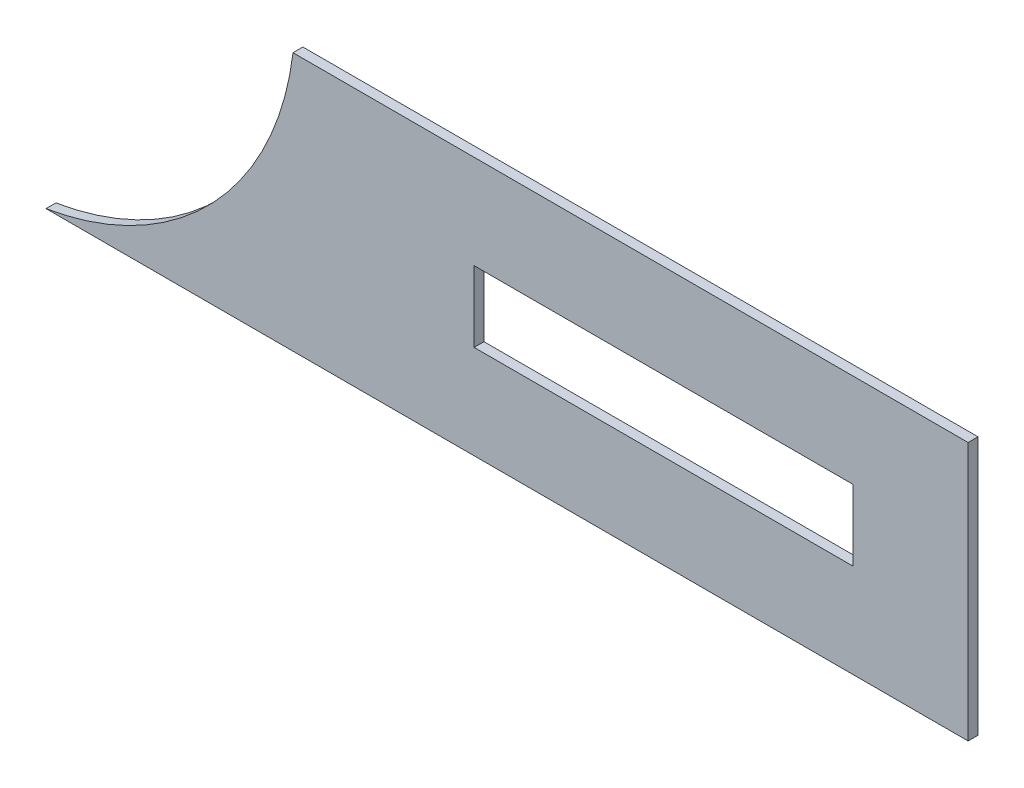
SolidWorks part; units mm, degrees
ref_plane "Спереди" through (0, 0, 0) normal (0, 0, 1) x (1, 0, 0)
ref_plane "Сверху" through (0, 0, 0) normal (0, 1, 0) x (1, 0, 0)
ref_plane "Справа" through (0, 0, 0) normal (1, 0, 0) x (0, 0, -1)
sketch "Эскиз1" plane through (0, 0, 0) normal (0, 0, 1) x (1, 0, 0)
  line L1 (0, 0) -> (56, 0)
  line L2 (26, 5.7) -> (49, 5.7)
  line L3 (15, 15.7) -> (56, 15.7)
  line L4 (56, 0) -> (56, 15.7)
  line L5 (26, 5.7) -> (26, 10)
  line L6 (26, 10) -> (49, 10)
  line L7 (49, 5.7) -> (49, 10)
  arc A0 (0, 0) -> (15, 15.7) centre (-2.9872, 17.8697) ccw
  point P10 (56, 7.85)
  point P11 (49, 7.85)
  dimension "D3" = 41
  dimension "D1" = 15.7
  dimension "D2" = 56
  dimension "D4" = 23
  dimension "D5" = 4.3
  dimension "D6" = 7
extrude "Бобышка-Вытянуть1" add sketch "Эскиз1" along normal blind 0.6
